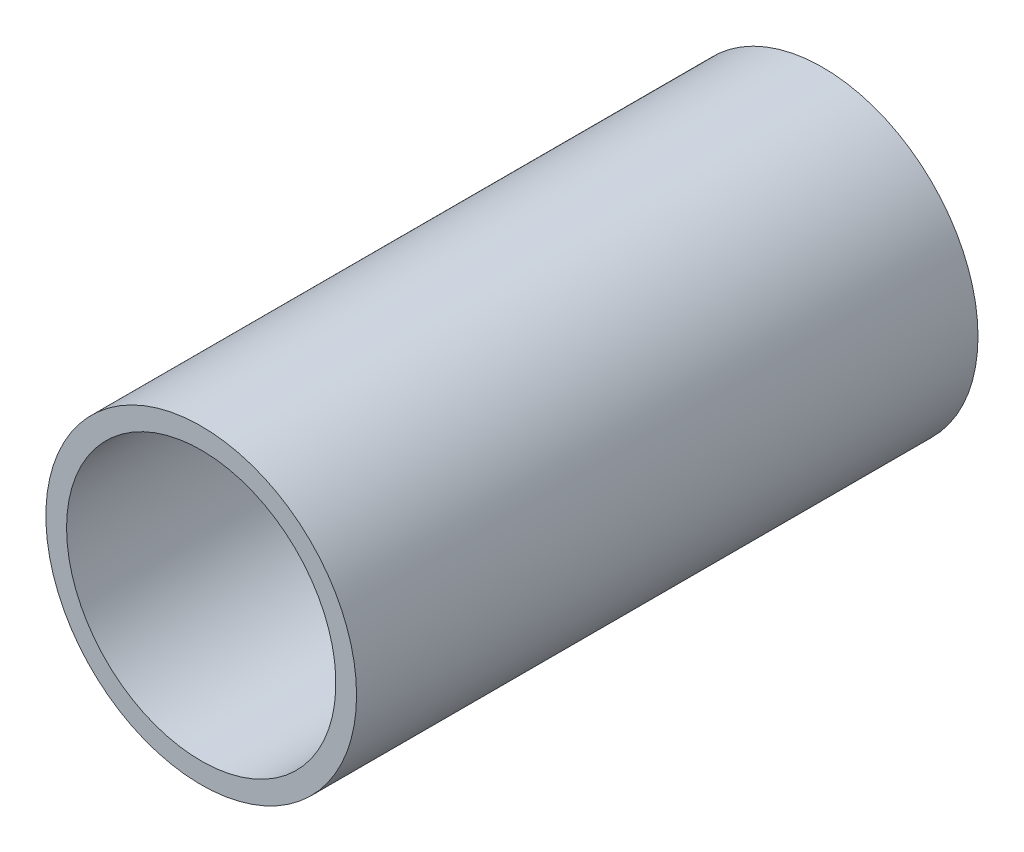
SolidWorks part; units mm, degrees
ref_plane "前视基准面" through (0, 0, 0) normal (0, 0, 1) x (1, 0, 0)
ref_plane "上视基准面" through (0, 0, 0) normal (0, 1, 0) x (1, 0, 0)
ref_plane "右视基准面" through (0, 0, 0) normal (1, 0, 0) x (0, 0, -1)
sketch "草图1" plane through (0, 0, 0) normal (0, 0, 1) x (1, 0, 0)
  circle A0 centre (0, 0) radius 15
  dimension "D1" = 30
extrude "凸台-拉伸1" add sketch "草图1" along normal blind 60
sketch "草图4" plane through (0, 0, 0) normal (0, 0, -1) x (-1, 0, 0)
  circle A0 centre (0, 0) radius 13
ref_plane "基准面4" through (0, 0, 20) normal (0, 0, 1) x (1, 0, 0)
sketch "草图6" plane through (0, 0, 20) normal (0, 0, 1) x (1, 0, 0)
  circle A0 centre (0, 0) radius 4
extrude "切除-拉伸1" cut sketch "草图4" against normal through all
